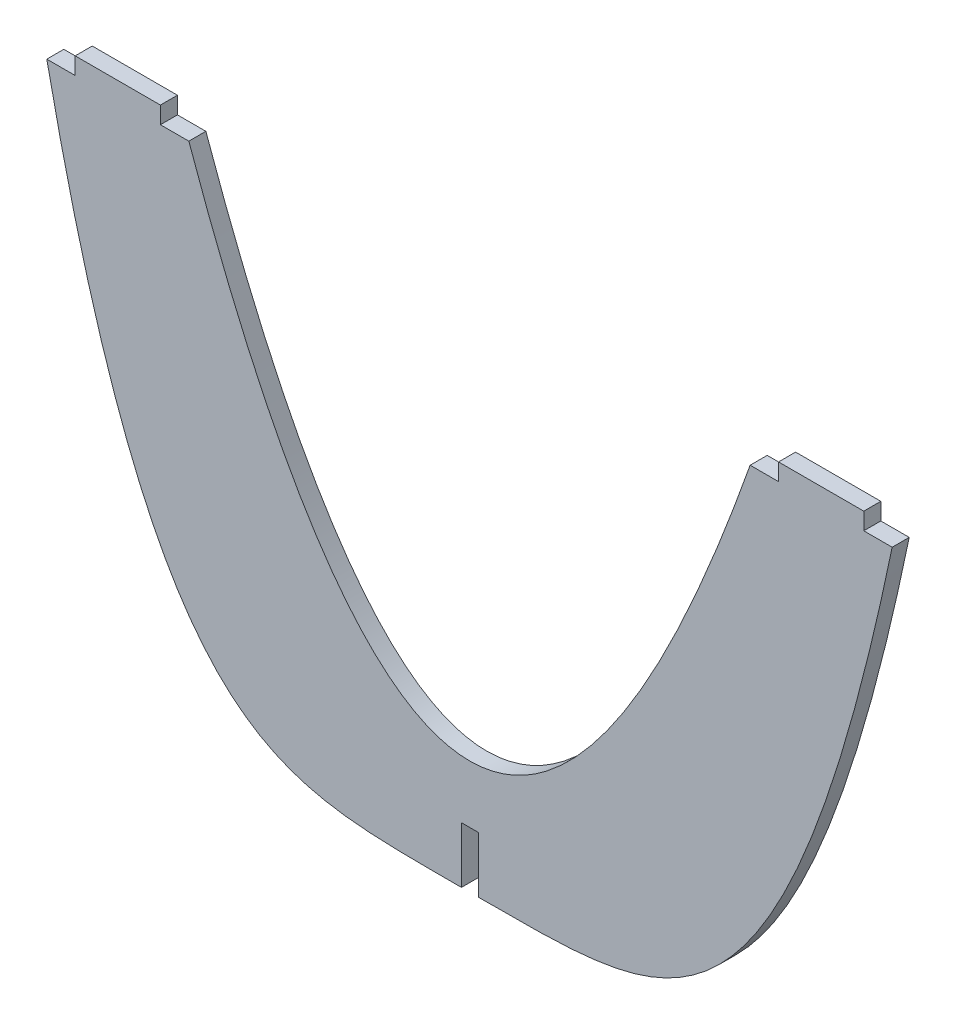
SolidWorks part; units mm, degrees
ref_plane "前视基准面" through (0, 0, 0) normal (0, 0, 1) x (1, 0, 0)
ref_plane "上视基准面" through (0, 0, 0) normal (0, 1, 0) x (1, 0, 0)
ref_plane "右视基准面" through (0, 0, 0) normal (1, 0, 0) x (0, 0, -1)
other "Configuration Table"
sketch "草图1" plane through (0, 0, 0) normal (0, 0, 1) x (1, 0, 0)
  line L8 (0, 0) -> (0, 135) construction
  line L21 (-74.4819, 89.7662) -> (-69.4819, 89.7662)
  line L22 (-69.4819, 89.7662) -> (-69.4819, 92.7662)
  line L23 (-69.4819, 92.7662) -> (-54.4819, 92.7662)
  line L24 (-54.4819, 92.7662) -> (-54.4819, 89.7662)
  line L25 (-54.4819, 89.7662) -> (-49.4819, 89.7662)
  line L26 (74.3181, 89.7662) -> (69.3181, 89.7662)
  line L27 (69.3181, 89.7662) -> (69.3181, 92.7662)
  line L28 (69.3181, 92.7662) -> (54.3181, 92.7662)
  line L29 (54.3181, 92.7662) -> (54.3181, 89.7662)
  line L30 (54.3181, 89.7662) -> (49.3181, 89.7662)
  line L32 (0, 0) -> (1.5, 0)
  spline S0 degree 4 poles (-79.3638, 115.7493) (-39.7228, -115.7493) (-0.0819, 115.7493) (39.5591, -115.7493) (79.2001, 115.7493) knots 0 0 0 0 0 1 1 1 1 1 construction
  spline S1 degree 4 poles (-74.4819, 89.7662) (-37.2819, -89.7662) (-0.0819, 89.7662) (37.1181, -89.7662) (74.3181, 89.7662) knots 0.030788 0.030788 0.030788 0.030788 0.030788 0.969212 0.969212 0.969212 0.969212 0.969212
  spline S2 degree 2 poles (-49.4819, 89.7662) (0.0272, -49.7663) (49.3181, 89.7662) knots 0 0 0 1 1 1
extrude "凸台-拉伸1" add sketch "草图1" along normal blind 3
sketch "草图4" plane through (0, 0, 3) normal (0, 0, 1) x (1, 0, 0)
  line L0 (0, 32.6289) -> (0, -12.716) construction
  line L2 (-1.5, 9.87) -> (1.5, 9.87)
  line L3 (-1.5, 9.87) -> (-1.5, 0)
  line L4 (-1.5, 0) -> (1.5, 0)
  line L5 (1.5, 9.87) -> (1.5, 0)
  spline S0 degree 4 poles (-74.4819, 89.7662) (-37.2819, -89.7662) (-0.0819, 89.7662) (37.1181, -89.7662) (74.3181, 89.7662) knots 0.030788 0.030788 0.030788 0.030788 0.030788 0.969212 0.969212 0.969212 0.969212 0.969212 construction
  dimension "D1" = 9.87
  dimension "D2" = 3
extrude "切除-拉伸1" cut sketch "草图4" against normal blind 10
sketch "草图5" plane through (0, 0, 3) normal (0, 0, 1) x (1, 0, 0)
  line L0 (-1.5, 9.87) -> (-1.5, 0) construction
  line L1 (-1.5, 1.8656) -> (1.5, 1.8656)
  line L2 (-1.5, 1.8656) -> (-1.5, -0.96)
  line L3 (-1.5, -0.96) -> (1.5, -0.96)
  line L4 (1.5, 1.8656) -> (1.5, -0.96)
extrude "切除-拉伸2" cut sketch "草图5" against normal blind 10
